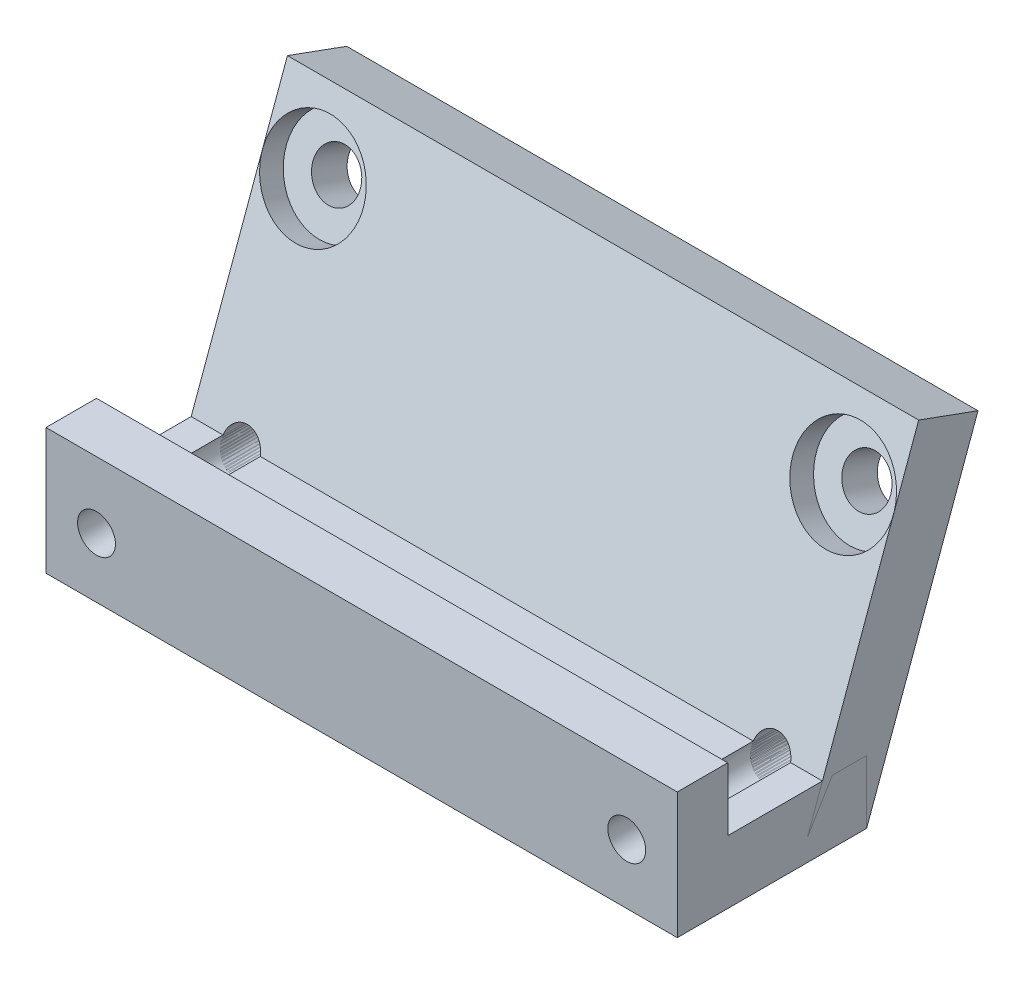
SolidWorks part; units mm, degrees
ref_plane "Front Plane" through (0, 0, 0) normal (0, 0, 1) x (1, 0, 0)
ref_plane "Top Plane" through (0, 0, 0) normal (0, 1, 0) x (1, 0, 0)
ref_plane "Right Plane" through (0, 0, 0) normal (1, 0, 0) x (0, 0, -1)
sketch "Esquisse15" plane through (0, 0, 0) normal (0, 1, 0) x (1, 0, 0)
  line L1 (-25, 7.5) -> (25, 7.5)
  line L2 (-25, 7.5) -> (-25, -7.5)
  line L3 (-25, -7.5) -> (25, -7.5)
  line L4 (25, 7.5) -> (25, -7.5)
  line L5 (-25, 7.5) -> (25, -7.5) construction
  line L6 (-25, -7.5) -> (25, 7.5) construction
  point P0 (0, 0)
extrude "Boss.-Extru.6" add sketch "Esquisse15" along normal blind 5
sketch "Esquisse16" plane through (0, 5, 0) normal (0, 1, 0) x (1, 0, 0)
  line L0 (25, -7.5) -> (25, 7.5) construction
  line L1 (-25, -7.5) -> (25, -7.5)
  line L2 (-25, -7.5) -> (-25, -3.5)
  line L3 (-25, -3.5) -> (25, -3.5)
  line L4 (25, -7.5) -> (25, -3.5)
extrude "Boss.-Extru.7" add sketch "Esquisse16" along normal blind 5
ref_plane "Plan4" through (0, 0, 0) normal (1, 0, 0) x (0, 0, -1)
ref_plane "Plan10" through (0, -2.4105, -6.6227) normal (0, -0.342, -0.9397) x (-1, 0, 0)
sketch "Esquisse20" plane through (0, -2.4105, -6.6227) normal (0, -0.342, -0.9397) x (-1, 0, 0)
  line L0 (25, 7.2636) -> (25, 2.5652) construction
  line L1 (-25, 2.5652) -> (25, 2.5652)
  line L2 (-25, 2.5652) -> (-25, 28.3582)
  line L3 (-25, 28.3582) -> (25, 28.3582)
  line L4 (25, 2.5652) -> (25, 28.3582)
  point P5 (0, 0)
extrude "Boss.-Extru.8" add sketch "Esquisse20" against normal blind 5 separate body
sketch "Esquisse22" plane through (0, -2.4105, -6.6227) normal (0, -0.342, -0.9397) x (1, 0, 0)
  line L0 (0, -14.3568) -> (0, 14.3568) construction
  line L1 (25, -2.5652) -> (-25, -2.5652) construction
  circle A0 centre (21, -22.5652) radius 1.8841
  dimension "D1" = 21
  dimension "D2" = 20
extrude "Enlèv. mat.-Extru.7" cut sketch "Esquisse22" against normal through all
mirror "Symétrie5" about plane through (0, 0, 0) normal (1, 0, 0) of "Enlèv. mat.-Extru.7"
sketch "Esquisse23" plane through (0, 0, 7.5) normal (0, 0, 1) x (1, 0, 0)
  line L0 (0, -14.3568) -> (0, 14.3568) construction
  circle A0 centre (21, 4.7412) radius 1.5
  dimension "D1" = 21
extrude "Enlèv. mat.-Extru.8" cut sketch "Esquisse23" against normal through all
sketch "Esquisse24" plane through (0, -0.7004, -1.9242) normal (0, 0.342, 0.9397) x (1, 0, 0)
  circle A0 centre (21, 22.5652) radius 3.9983
extrude "Enlèv. mat.-Extru.9" cut sketch "Esquisse24" against normal blind 2
mirror "Symétrie7" about plane through (0, 0, 0) normal (1, 0, 0) of "Enlèv. mat.-Extru.9"
sketch "Esquisse26" plane through (0, 0, 0) normal (0, -1, 0) x (1, 0, 0)
  line L0 (0, -14.3568) -> (0, 14.3568) construction
  line L1 (-20, 2) -> (20, 2)
  line L2 (-20, 2) -> (-20, 0)
  line L3 (-20, 0) -> (20, 0)
  line L4 (20, 2) -> (20, 0)
  point P4 (0, 0)
extrude "Enlèv. mat.-Extru.10" cut sketch "Esquisse26" against normal through all
ref_plane "Plan12" through (0, 0, -7.5) normal (0, 0, 1) x (1, 0, 0)
sketch "Esquisse27" plane through (0, 0, -7.5) normal (0, 0, 1) x (1, 0, 0)
  circle A0 centre (21, 4.7412) radius 3.9973
extrude "Enlèv. mat.-Extru.11" cut sketch "Esquisse27" against normal blind 6
mirror "Symétrie8" about plane through (0, 0, 0) normal (1, 0, 0) of "Enlèv. mat.-Extru.11"
sketch "Esquisse28" plane through (0, 0, 7.5) normal (0, 0, 1) x (1, 0, 0)
  line L0 (0, -14.3568) -> (0, 14.3568) construction
  circle A0 centre (-21, 4.7379) radius 1.5
  dimension "D1" = 21
extrude "Enlèv. mat.-Extru.12" cut sketch "Esquisse28" against normal through all
